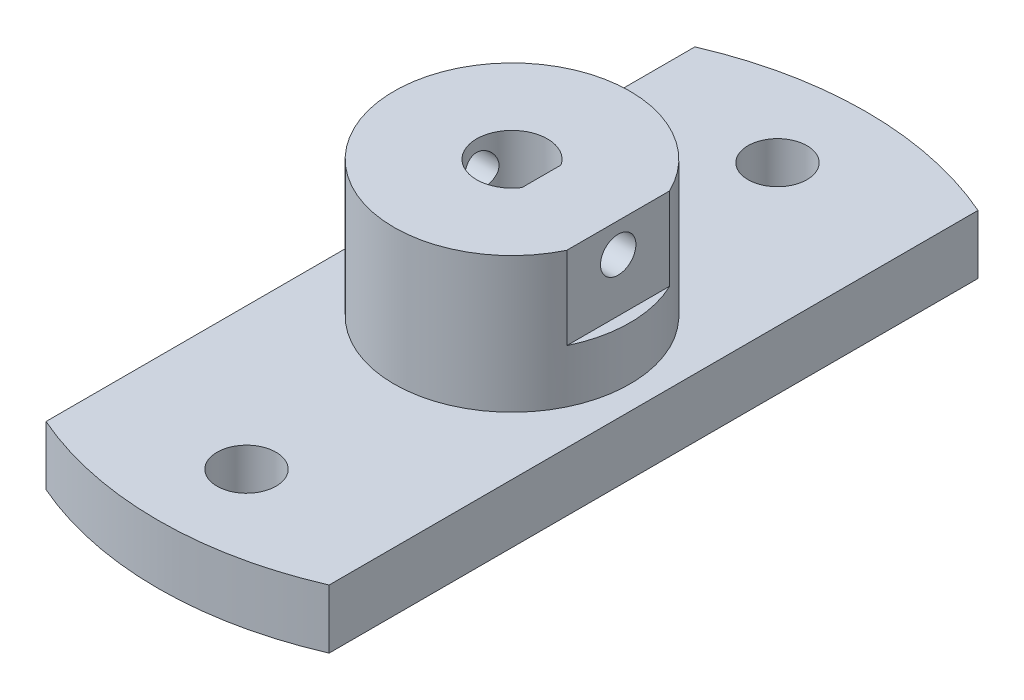
SolidWorks part; units mm, degrees
ref_plane "前视基准面" through (0, 0, 0) normal (0, 0, 1) x (1, 0, 0)
ref_plane "上视基准面" through (0, 0, 0) normal (0, 1, 0) x (1, 0, 0)
ref_plane "右视基准面" through (0, 0, 0) normal (1, 0, 0) x (0, 0, -1)
other "Configuration Table"
sketch "草图1" plane through (0, 0, 0) normal (0, 1, 0) x (1, 0, 0)
  line L0 (0, 50.9432) -> (0, -56.1744) construction
  line L1 (12, 27.4955) -> (12, -27.4955)
  line L2 (-12, 27.4955) -> (-12, -27.4955)
  arc A1 (12, 27.4955) -> (-12, 27.4955) centre (0, 0) ccw
  arc A2 (-12, -27.4955) -> (12, -27.4955) centre (0, 0) ccw
  circle A3 centre (0, 22.5) radius 2.5
  circle A4 centre (0, -22.5) radius 2.5
  dimension "D2" = 60
  dimension "D4" = 5
  dimension "D5" = 5
  dimension "D3" = 12
  dimension "D6" = 45
  dimension "D7" = 22.5
extrude "凸台-拉伸1" add sketch "草图1" along normal blind 5
sketch "草图2" plane through (0, 5, 0) normal (0, 1, 0) x (1, 0, 0)
  line L0 (0, 37.6002) -> (0, -39.8959) construction
  circle A0 centre (0, 0) radius 10
  dimension "D1" = 20
extrude "凸台-拉伸2" add sketch "草图2" along normal blind 11.5
sketch "草图3" plane through (0, 16.5, 0) normal (0, 1, 0) x (1, 0, 0)
  line L0 (9, 4.3589) -> (9, -4.3589)
  circle A0 centre (0, 0) radius 10 construction
  arc A1 (9, -4.3589) -> (9, 4.3589) centre (0, 0) ccw
  dimension "D1" = 9
extrude "切除-拉伸1" cut sketch "草图3" against normal blind 7
sketch "草图4" plane through (0, 16.5, 0) normal (0, 1, 0) x (1, 0, 0)
  line L0 (2.5, 1.6583) -> (2.5, -1.6583)
  arc A0 (2.5, 1.6583) -> (2.5, -1.6583) centre (0, 0) ccw
  dimension "D1" = 6
  dimension "D2" = 2.5
extrude "切除-拉伸2" cut sketch "草图4" against normal blind 11.5
sketch "草图5" plane through (0, 5, 0) normal (0, 1, 0) x (1, 0, 0)
  circle A1 centre (0, 0) radius 3
  dimension "D1" = 6
extrude "切除-拉伸3" cut sketch "草图5" against normal blind 11.5
sketch "草图6" plane through (9, 0, 0) normal (1, 0, 0) x (0, 0, -1)
  line L0 (0, 25.1996) -> (0, -10.5156) construction
  line L1 (-27.4955, 5) -> (27.4955, 5) construction
  circle A0 centre (0, 14) radius 1.5
  dimension "D1" = 3
  dimension "D2" = 9
extrude "切除-拉伸4" cut sketch "草图6" against normal through all
